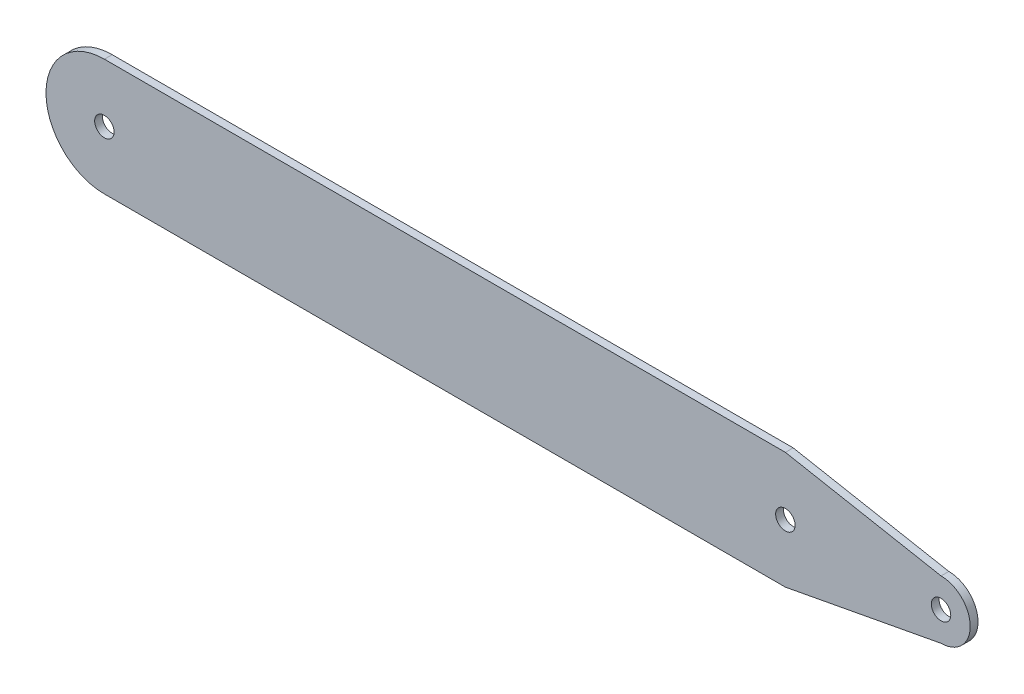
SolidWorks part; units mm, degrees
ref_plane "前视基准面" through (0, 0, 0) normal (0, 0, 1) x (1, 0, 0)
ref_plane "上视基准面" through (0, 0, 0) normal (0, 1, 0) x (1, 0, 0)
ref_plane "右视基准面" through (0, 0, 0) normal (1, 0, 0) x (0, 0, -1)
sketch "草图1" plane through (0, 0, 0) normal (0, 0, 1) x (1, 0, 0)
  line L0 (428.5429, -15.1457) -> (348.5429, -30.1457)
  line L1 (-1.4571, -0.1457) -> (348.5429, -0.1457) construction
  line L4 (348.5429, -0.1457) -> (428.5429, -0.1457) construction
  line L5 (428.5429, 14.8543) -> (348.5429, 29.8543)
  line L6 (348.5429, -30.1457) -> (-1.4571, -30.1457)
  line L7 (-1.4571, 29.8543) -> (348.5429, 29.8543)
  circle A0 centre (428.5429, -0.1457) radius 5
  circle A1 centre (-1.4571, -0.1457) radius 5
  circle A4 centre (-1.4571, -0.1457) radius 30 construction
  circle A11 centre (348.5429, -0.1457) radius 5
  circle A14 centre (348.5429, -0.1457) radius 30 construction
  circle A15 centre (428.5429, -0.1457) radius 15 construction
  arc A16 (428.5429, -15.1457) -> (428.5429, 14.8543) centre (428.5429, -0.1457) ccw
  arc A17 (-1.4571, -30.1457) -> (-1.4571, 29.8543) centre (-1.4571, -0.1457) cw
  dimension "D1" = 350
  dimension "D2" = 10
  dimension "D4" = 10
  dimension "D7" = 80
extrude "凸台-拉伸1" add sketch "草图1" along normal blind 4
